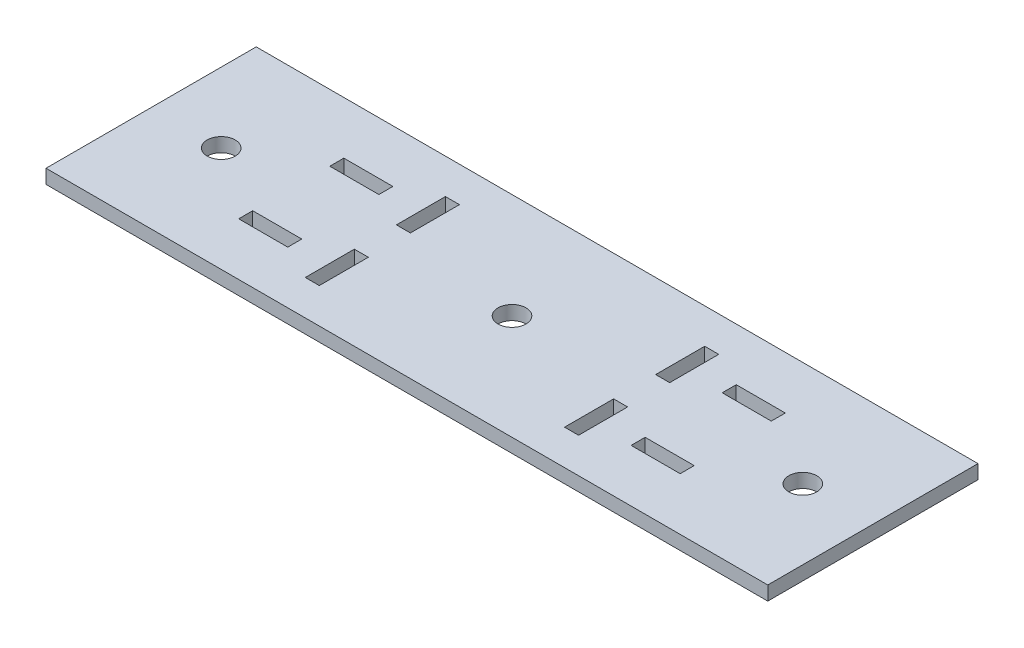
SolidWorks part; units mm, degrees
ref_plane "Front Plane" through (0, 0, 0) normal (0, 0, 1) x (1, 0, 0)
ref_plane "Top Plane" through (0, 0, 0) normal (0, 1, 0) x (1, 0, 0)
ref_plane "Right Plane" through (0, 0, 0) normal (1, 0, 0) x (0, 0, -1)
sketch "Sketch1" plane through (0, 0, 0) normal (0, 1, 0) x (1, 0, 0)
  line L1 (-62.7698, 6.0364) -> (40.2302, 6.0364)
  line L2 (-62.7698, 6.0364) -> (-62.7698, -23.9636)
  line L3 (-62.7698, -23.9636) -> (40.2302, -23.9636)
  line L4 (40.2302, 6.0364) -> (40.2302, -23.9636)
  line L5 (-42.7698, -14.4636) -> (-35.7698, -14.4636)
  line L6 (-42.7698, -14.4636) -> (-42.7698, -16.4636)
  line L7 (-42.7698, -16.4636) -> (-35.7698, -16.4636)
  line L8 (-35.7698, -14.4636) -> (-35.7698, -16.4636)
  line L9 (-42.7698, -1.4636) -> (-35.7698, -1.4636)
  line L10 (-42.7698, -1.4636) -> (-42.7698, -3.4636)
  line L11 (-42.7698, -3.4636) -> (-35.7698, -3.4636)
  line L12 (-35.7698, -1.4636) -> (-35.7698, -3.4636)
  line L13 (13.2302, -1.4636) -> (20.2302, -1.4636)
  line L14 (13.2302, -1.4636) -> (13.2302, -3.4636)
  line L15 (13.2302, -3.4636) -> (20.2302, -3.4636)
  line L16 (20.2302, -1.4636) -> (20.2302, -3.4636)
  line L17 (13.2302, -14.4636) -> (20.2302, -14.4636)
  line L18 (13.2302, -14.4636) -> (13.2302, -16.4636)
  line L19 (13.2302, -16.4636) -> (20.2302, -16.4636)
  line L20 (20.2302, -14.4636) -> (20.2302, -16.4636)
  line L21 (-30.7698, 1.0364) -> (-28.7698, 1.0364)
  line L22 (-30.7698, 1.0364) -> (-30.7698, -5.9636)
  line L23 (-30.7698, -5.9636) -> (-28.7698, -5.9636)
  line L24 (-28.7698, 1.0364) -> (-28.7698, -5.9636)
  line L25 (-30.7698, -11.9636) -> (-28.7698, -11.9636)
  line L26 (-30.7698, -11.9636) -> (-30.7698, -18.9636)
  line L27 (-30.7698, -18.9636) -> (-28.7698, -18.9636)
  line L28 (-28.7698, -11.9636) -> (-28.7698, -18.9636)
  line L29 (8.2302, -18.9636) -> (6.2302, -18.9636)
  line L30 (8.2302, -18.9636) -> (8.2302, -11.9636)
  line L31 (8.2302, -11.9636) -> (6.2302, -11.9636)
  line L32 (6.2302, -18.9636) -> (6.2302, -11.9636)
  line L33 (8.2302, -5.9636) -> (6.2302, -5.9636)
  line L34 (8.2302, -5.9636) -> (8.2302, 1.0364)
  line L35 (8.2302, 1.0364) -> (6.2302, 1.0364)
  line L36 (6.2302, -5.9636) -> (6.2302, 1.0364)
  circle A0 centre (-52.7698, -8.9636) radius 2
  circle A1 centre (30.2302, -8.9636) radius 2
  circle A2 centre (-11.2698, -8.9636) radius 2
  point P42 (-30.7698, -2.4636)
  point P43 (8.2302, -2.4636)
  point P44 (8.2302, -15.4636)
  point P45 (7.2302, -11.9636)
  dimension "D21" = 4
  dimension "D22" = 4
  dimension "D24" = 10
  dimension "D25" = 10
  dimension "D27" = 15
  dimension "D29" = 4
  dimension "D31" = 51.5
  dimension "D1" = 30
  dimension "D2" = 103
  dimension "D3" = 7
  dimension "D4" = 7
  dimension "D5" = 7
  dimension "D6" = 7
  dimension "D7" = 2
  dimension "D8" = 2
  dimension "D9" = 2
  dimension "D10" = 2
  dimension "D11" = 20
  dimension "D12" = 20
  dimension "D13" = 20
  dimension "D14" = 20
  dimension "D15" = 7.5
  dimension "D16" = 7.5
  dimension "D17" = 11
  dimension "D18" = 7.5
  dimension "D19" = 11
  dimension "D20" = 7.5
  dimension "D23" = 10
  dimension "D26" = 10
  dimension "D28" = 15
  dimension "D30" = 15
  dimension "D32" = 5
  dimension "D33" = 5
  dimension "D34" = 5
  dimension "D35" = 5
  dimension "D36" = 2
  dimension "D37" = 2
  dimension "D38" = 2
  dimension "D39" = 2
  dimension "D40" = 7
  dimension "D41" = 7
  dimension "D42" = 5
  dimension "D43" = 5
  dimension "D44" = 6
  dimension "D45" = 5
  dimension "D46" = 7
  dimension "D47" = 5
  dimension "D48" = 7
  dimension "D49" = 6
extrude "Boss-Extrude1" add sketch "Sketch1" along normal blind 2
